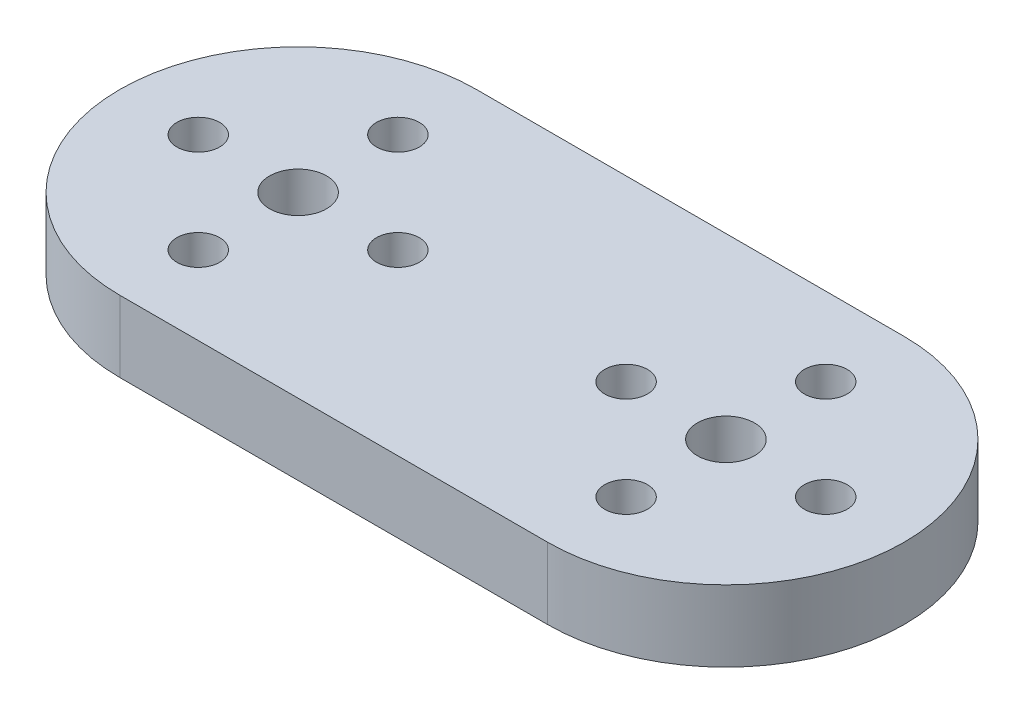
SolidWorks part; units mm, degrees
ref_plane "前视基准面" through (0, 0, 0) normal (0, 0, 1) x (1, 0, 0)
ref_plane "上视基准面" through (0, 0, 0) normal (0, 1, 0) x (1, 0, 0)
ref_plane "右视基准面" through (0, 0, 0) normal (1, 0, 0) x (0, 0, -1)
other "Configuration Table"
sketch "草图1" plane through (0, 0, 0) normal (0, 1, 0) x (1, 0, 0)
  line L0 (15, -12.5) -> (15, 12.5) construction
  line L1 (0, 12.5) -> (30, 12.5)
  line L2 (0, -12.5) -> (30, -12.5)
  arc A0 (0, 12.5) -> (0, -12.5) centre (0, 0) ccw
  arc A1 (30, -12.5) -> (30, 12.5) centre (30, 0) ccw
  circle A2 centre (30, 0) radius 2
  circle A4 centre (0, 0) radius 2
  circle A5 centre (0, 0) radius 7 construction
  circle A6 centre (7, 0) radius 1.5
  circle A7 centre (0, 7) radius 1.5
  circle A8 centre (-7, 0) radius 1.5
  circle A9 centre (0, -7) radius 1.5
  circle A10 centre (23, 0) radius 1.5
  circle A11 centre (30, -7) radius 1.5
  circle A12 centre (37, 0) radius 1.5
  circle A13 centre (30, 7) radius 1.5
  dimension "D1" = 25
  dimension "D3" = 25
  dimension "D4" = 4
  dimension "D5" = 4
  dimension "D6" = 14
  dimension "D7" = 3
  dimension "D8" = 3
  dimension "D9" = 3
  dimension "D10" = 3
  dimension "D2" = 30
extrude "凸台-拉伸1" add sketch "草图1" along normal blind 5
